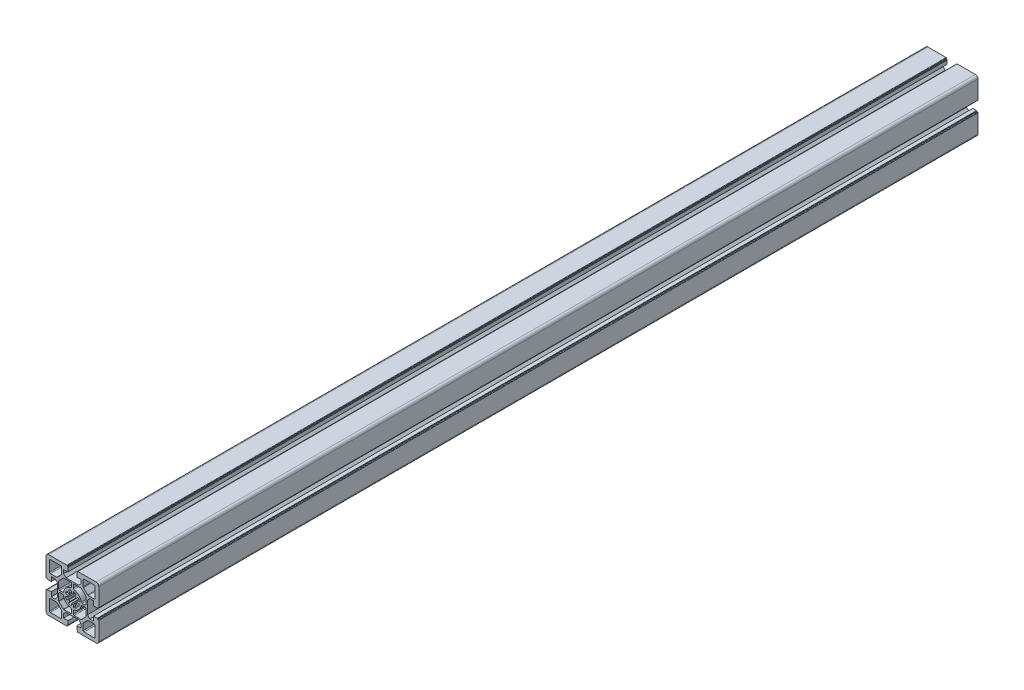
SolidWorks part; units mm, degrees
ref_plane "Front Plane" through (0, 0, 0) normal (0, 0, 1) x (1, 0, 0)
ref_plane "Top Plane" through (0, 0, 0) normal (0, 1, 0) x (1, 0, 0)
ref_plane "Right Plane" through (0, 0, 0) normal (1, 0, 0) x (0, 0, -1)
sketch "Sketch1" plane through (0, 0, 0) normal (0, 0, 1) x (1, 0, 0)
  line L0 (25, 12.3) -> (17.9642, 12.3)
  line L1 (17.2571, 12.5929) -> (12.5929, 17.2571)
  line L2 (12.3, 17.9642) -> (12.3, 25)
  line L3 (25, 26) -> (13.3, 26)
  line L4 (26, 13.3) -> (26, 25)
  line L5 (-0.8683, 4.924) -> (-1.3892, 7.8785)
  line L6 (-4.5886, 6.5532) -> (-2.8679, 4.0958)
  line L7 (-4.0958, 2.8679) -> (-6.5532, 4.5886)
  line L8 (-7.8785, 1.3892) -> (-4.9241, 0.8683)
  line L9 (14.5, 1) -> (10.9691, 1)
  line L10 (15.5, 2) -> (15.5, 9.9003)
  line L11 (15.3535, 10.2538) -> (10.2538, 15.3536)
  line L12 (9.9002, 15.5) -> (2, 15.5)
  line L13 (1, 10.9692) -> (1, 14.5)
  line L14 (7.25, 17) -> (0, 17)
  line L15 (10.05, 19.8) -> (7.25, 17)
  line L16 (10.05, 24) -> (10.05, 19.8)
  line L17 (5, 24) -> (10.05, 24)
  line L18 (5, 28.2) -> (5, 24)
  line L19 (5.5, 28.5) -> (5.3, 28.5)
  line L20 (5.8, 28.8) -> (5.8, 29.5)
  line L21 (27, 30) -> (6.3, 30)
  line L22 (30, 6.3) -> (30, 27)
  line L23 (29.5, 5.8) -> (28.8, 5.8)
  line L24 (28.5, 5.3) -> (28.5, 5.5)
  line L25 (24, 5) -> (28.2, 5)
  line L26 (24, 10.05) -> (24, 5)
  line L27 (19.8, 10.05) -> (24, 10.05)
  line L28 (17, 7.25) -> (19.8, 10.05)
  line L29 (17, 7.25) -> (17, 0)
  line L30 (7.8784, 1.3892) -> (4.924, 0.8683)
  line L31 (4.0957, 2.8679) -> (6.5532, 4.5886)
  line L32 (4.5886, 6.5532) -> (2.8679, 4.0958)
  line L33 (0.8682, 4.924) -> (1.3892, 7.8785)
  line L34 (-25, -12.3) -> (-17.9642, -12.3)
  line L35 (-17.2571, -12.5929) -> (-12.5929, -17.2571)
  line L36 (-12.3, -17.9642) -> (-12.3, -25)
  line L37 (-25, -26) -> (-13.3, -26)
  line L38 (-26, -13.3) -> (-26, -25)
  line L39 (-14.5, -1) -> (-10.9692, -1)
  line L40 (-15.5, -2) -> (-15.5, -9.9002)
  line L41 (-17, 7.25) -> (-17, 0)
  line L42 (-17, 7.25) -> (-19.8, 10.05)
  line L43 (-19.8, 10.05) -> (-24, 10.05)
  line L44 (-24, 10.05) -> (-24, 5)
  line L45 (-24, 5) -> (-28.2, 5)
  line L46 (-28.5, 5.3) -> (-28.5, 5.5)
  line L47 (-29.5, 5.8) -> (-28.8, 5.8)
  line L48 (-30, 6.3) -> (-30, 27)
  line L49 (-27, 30) -> (-6.3, 30)
  line L50 (-5.8, 28.8) -> (-5.8, 29.5)
  line L51 (-5.5, 28.5) -> (-5.3, 28.5)
  line L52 (-5, 28.2) -> (-5, 24)
  line L53 (-5, 24) -> (-10.05, 24)
  line L54 (-10.05, 24) -> (-10.05, 19.8)
  line L55 (-10.05, 19.8) -> (-7.25, 17)
  line L56 (-7.25, 17) -> (0, 17)
  line L57 (-15.3536, -10.2538) -> (-10.2538, -15.3535)
  line L58 (-9.9003, -15.5) -> (-2, -15.5)
  line L59 (-1, -10.9691) -> (-1, -14.5)
  line L60 (-7.25, -17) -> (0, -17)
  line L61 (-10.05, -19.8) -> (-7.25, -17)
  line L62 (-10.05, -24) -> (-10.05, -19.8)
  line L63 (-5, -24) -> (-10.05, -24)
  line L64 (-5, -28.2) -> (-5, -24)
  line L65 (-5.5, -28.5) -> (-5.3, -28.5)
  line L66 (-5.8, -28.8) -> (-5.8, -29.5)
  line L67 (-27, -30) -> (-6.3, -30)
  line L68 (-30, -6.3) -> (-30, -27)
  line L69 (-29.5, -5.8) -> (-28.8, -5.8)
  line L70 (-28.5, -5.3) -> (-28.5, -5.5)
  line L71 (-24, -5) -> (-28.2, -5)
  line L72 (-24, -10.05) -> (-24, -5)
  line L73 (-19.8, -10.05) -> (-24, -10.05)
  line L74 (-17, -7.25) -> (-19.8, -10.05)
  line L75 (-17, 0) -> (-17, -7.25)
  line L76 (0.8682, -4.924) -> (1.3892, -7.8784)
  line L77 (4.5886, -6.5532) -> (2.8679, -4.0957)
  line L78 (4.0957, -2.8679) -> (6.5532, -4.5886)
  line L79 (7.8784, -1.3892) -> (4.924, -0.8682)
  line L80 (17, 0) -> (17, -7.25)
  line L81 (17, -7.25) -> (19.8, -10.05)
  line L82 (19.8, -10.05) -> (24, -10.05)
  line L83 (24, -10.05) -> (24, -5)
  line L84 (24, -5) -> (28.2, -5)
  line L85 (28.5, -5.3) -> (28.5, -5.5)
  line L86 (29.5, -5.8) -> (28.8, -5.8)
  line L87 (30, -6.3) -> (30, -27)
  line L88 (27, -30) -> (6.3, -30)
  line L89 (5.8, -28.8) -> (5.8, -29.5)
  line L90 (5.5, -28.5) -> (5.3, -28.5)
  line L91 (5, -28.2) -> (5, -24)
  line L92 (5, -24) -> (10.05, -24)
  line L93 (10.05, -24) -> (10.05, -19.8)
  line L94 (10.05, -19.8) -> (7.25, -17)
  line L95 (7.25, -17) -> (0, -17)
  line L96 (1, -10.9691) -> (1, -14.5)
  line L97 (9.9002, -15.5) -> (2, -15.5)
  line L98 (15.3535, -10.2538) -> (10.2538, -15.3535)
  line L99 (15.5, -2) -> (15.5, -9.9002)
  line L100 (-1, 10.9692) -> (-1, 14.5)
  line L101 (-9.9003, 15.5) -> (-2, 15.5)
  line L102 (-15.3536, 10.2538) -> (-10.2538, 15.3536)
  line L103 (-15.5, 2) -> (-15.5, 9.9003)
  line L104 (-14.5, 1) -> (-10.9692, 1)
  line L105 (-26, 13.3) -> (-26, 25)
  line L106 (-25, 26) -> (-13.3, 26)
  line L107 (-12.3, 17.9642) -> (-12.3, 25)
  line L108 (-17.2571, 12.5929) -> (-12.5929, 17.2571)
  line L109 (-25, 12.3) -> (-17.9642, 12.3)
  line L110 (14.5, -1) -> (10.9691, -1)
  line L111 (-7.8785, -1.3892) -> (-4.9241, -0.8682)
  line L112 (-4.0958, -2.8679) -> (-6.5532, -4.5886)
  line L113 (-4.5886, -6.5532) -> (-2.8679, -4.0957)
  line L114 (-0.8683, -4.924) -> (-1.3892, -7.8784)
  line L115 (26, -13.3) -> (26, -25)
  line L116 (25, -26) -> (13.3, -26)
  line L117 (12.3, -17.9642) -> (12.3, -25)
  line L118 (17.2571, -12.5929) -> (12.5929, -17.2571)
  line L119 (25, -12.3) -> (17.9642, -12.3)
  line L120 (0, 0) -> (0, 50.387) construction
  line L121 (0, 0) -> (0, -41.9308) construction
  line L122 (0, 0) -> (51.9943, 0) construction
  line L123 (0, 0) -> (-54.8745, 0) construction
  arc A0 (17.9642, 12.3) -> (17.2571, 12.5929) centre (17.9642, 13.3) cw
  arc A1 (12.5929, 17.2571) -> (12.3, 17.9642) centre (13.3, 17.9642) cw
  arc A2 (12.3, 25) -> (13.3, 26) centre (13.3, 25) cw
  arc A3 (25, 26) -> (26, 25) centre (25, 25) cw
  arc A4 (26, 13.3) -> (25, 12.3) centre (25, 13.3) cw
  arc A5 (0, 5) -> (-0.8683, 4.924) centre (0, 0) ccw
  arc A6 (-1.3892, 7.8785) -> (-4.5886, 6.5532) centre (0, 0) ccw
  arc A7 (-2.8679, 4.0958) -> (-4.0958, 2.8679) centre (0, 0) ccw
  arc A8 (-6.5532, 4.5886) -> (-7.8785, 1.3892) centre (0, 0) ccw
  arc A9 (-4.9241, 0.8683) -> (-4.9241, -0.8682) centre (0, 0) ccw
  arc A10 (15.5, 2) -> (14.5, 1) centre (14.5, 2) cw
  arc A11 (15.3535, 10.2538) -> (15.5, 9.9003) centre (15, 9.9003) cw
  arc A12 (9.9002, 15.5) -> (10.2538, 15.3536) centre (9.9002, 15) cw
  arc A13 (1, 14.5) -> (2, 15.5) centre (2, 14.5) cw
  arc A14 (1.8206, 9.9854) -> (1, 10.9692) centre (2, 10.9692) cw
  arc A15 (1.8206, 9.9854) -> (9.9853, 1.8206) centre (0, 0) cw
  arc A16 (10.9691, 1) -> (9.9853, 1.8206) centre (10.9691, 2) cw
  arc A17 (5, 28.2) -> (5.3, 28.5) centre (5.3, 28.2) cw
  arc A18 (5.8, 28.8) -> (5.5, 28.5) centre (5.5, 28.8) cw
  arc A19 (5.8, 29.5) -> (6.3, 30) centre (6.3, 29.5) cw
  arc A20 (27, 30) -> (30, 27) centre (27, 27) cw
  arc A21 (30, 6.3) -> (29.5, 5.8) centre (29.5, 6.3) cw
  arc A22 (28.5, 5.5) -> (28.8, 5.8) centre (28.8, 5.5) cw
  arc A23 (28.5, 5.3) -> (28.2, 5) centre (28.2, 5.3) cw
  arc A24 (4.924, 0.8683) -> (4.924, -0.8682) centre (0, 0) cw
  arc A25 (6.5532, 4.5886) -> (7.8784, 1.3892) centre (0, 0) cw
  arc A26 (2.8679, 4.0958) -> (4.0957, 2.8679) centre (0, 0) cw
  arc A27 (1.3892, 7.8785) -> (4.5886, 6.5532) centre (0, 0) cw
  arc A28 (-28.5, 5.3) -> (-28.2, 5) centre (-28.2, 5.3) ccw
  arc A29 (-28.5, 5.5) -> (-28.8, 5.8) centre (-28.8, 5.5) ccw
  arc A30 (-30, 6.3) -> (-29.5, 5.8) centre (-29.5, 6.3) ccw
  arc A31 (-27, 30) -> (-30, 27) centre (-27, 27) ccw
  arc A32 (-5.8, 29.5) -> (-6.3, 30) centre (-6.3, 29.5) ccw
  arc A33 (-5.8, 28.8) -> (-5.5, 28.5) centre (-5.5, 28.8) ccw
  arc A34 (-5, 28.2) -> (-5.3, 28.5) centre (-5.3, 28.2) ccw
  arc A35 (0, 5) -> (0.8682, 4.924) centre (0, 0) cw
  arc A36 (-17.9642, -12.3) -> (-17.2571, -12.5929) centre (-17.9642, -13.3) cw
  arc A37 (-12.5929, -17.2571) -> (-12.3, -17.9642) centre (-13.3, -17.9642) cw
  arc A38 (-12.3, -25) -> (-13.3, -26) centre (-13.3, -25) cw
  arc A39 (-25, -26) -> (-26, -25) centre (-25, -25) cw
  arc A40 (-26, -13.3) -> (-25, -12.3) centre (-25, -13.3) cw
  arc A41 (-15.5, -2) -> (-14.5, -1) centre (-14.5, -2) cw
  arc A42 (-15.3536, -10.2538) -> (-15.5, -9.9002) centre (-15, -9.9002) cw
  arc A43 (-9.9003, -15.5) -> (-10.2538, -15.3535) centre (-9.9003, -15) cw
  arc A44 (-1, -14.5) -> (-2, -15.5) centre (-2, -14.5) cw
  arc A45 (-1.8206, -9.9853) -> (-1, -10.9691) centre (-2, -10.9691) cw
  arc A46 (-1.8206, -9.9853) -> (-9.9854, -1.8206) centre (0, 0) cw
  arc A47 (-10.9692, -1) -> (-9.9854, -1.8206) centre (-10.9692, -2) cw
  arc A48 (0, -4.9999) -> (0.8682, -4.924) centre (0, 0) ccw
  arc A49 (-5, -28.2) -> (-5.3, -28.5) centre (-5.3, -28.2) cw
  arc A50 (-5.8, -28.8) -> (-5.5, -28.5) centre (-5.5, -28.8) cw
  arc A51 (-5.8, -29.5) -> (-6.3, -30) centre (-6.3, -29.5) cw
  arc A52 (-27, -30) -> (-30, -27) centre (-27, -27) cw
  arc A53 (-30, -6.3) -> (-29.5, -5.8) centre (-29.5, -6.3) cw
  arc A54 (-28.5, -5.5) -> (-28.8, -5.8) centre (-28.8, -5.5) cw
  arc A55 (-28.5, -5.3) -> (-28.2, -5) centre (-28.2, -5.3) cw
  arc A56 (1.3892, -7.8784) -> (4.5886, -6.5532) centre (0, 0) ccw
  arc A57 (2.8679, -4.0957) -> (4.0957, -2.8679) centre (0, 0) ccw
  arc A58 (6.5532, -4.5886) -> (7.8784, -1.3892) centre (0, 0) ccw
  arc A59 (28.5, -5.3) -> (28.2, -5) centre (28.2, -5.3) ccw
  arc A60 (28.5, -5.5) -> (28.8, -5.8) centre (28.8, -5.5) ccw
  arc A61 (30, -6.3) -> (29.5, -5.8) centre (29.5, -6.3) ccw
  arc A62 (27, -30) -> (30, -27) centre (27, -27) ccw
  arc A63 (5.8, -29.5) -> (6.3, -30) centre (6.3, -29.5) ccw
  arc A64 (5.8, -28.8) -> (5.5, -28.5) centre (5.5, -28.8) ccw
  arc A65 (5, -28.2) -> (5.3, -28.5) centre (5.3, -28.2) ccw
  arc A66 (10.9691, -1) -> (9.9853, -1.8206) centre (10.9691, -2) ccw
  arc A67 (1.8206, -9.9853) -> (9.9853, -1.8206) centre (0, 0) ccw
  arc A68 (-10.9692, 1) -> (-9.9854, 1.8206) centre (-10.9692, 2) ccw
  arc A69 (-1.8206, 9.9854) -> (-9.9854, 1.8206) centre (0, 0) ccw
  arc A70 (-1.8206, 9.9854) -> (-1, 10.9692) centre (-2, 10.9692) ccw
  arc A71 (-1, 14.5) -> (-2, 15.5) centre (-2, 14.5) ccw
  arc A72 (-9.9003, 15.5) -> (-10.2538, 15.3536) centre (-9.9003, 15) ccw
  arc A73 (-15.3536, 10.2538) -> (-15.5, 9.9003) centre (-15, 9.9003) ccw
  arc A74 (-15.5, 2) -> (-14.5, 1) centre (-14.5, 2) ccw
  arc A75 (-26, 13.3) -> (-25, 12.3) centre (-25, 13.3) ccw
  arc A76 (-25, 26) -> (-26, 25) centre (-25, 25) ccw
  arc A77 (-12.3, 25) -> (-13.3, 26) centre (-13.3, 25) ccw
  arc A78 (-12.5929, 17.2571) -> (-12.3, 17.9642) centre (-13.3, 17.9642) ccw
  arc A79 (-17.9642, 12.3) -> (-17.2571, 12.5929) centre (-17.9642, 13.3) ccw
  arc A80 (1.8206, -9.9853) -> (1, -10.9691) centre (2, -10.9691) ccw
  arc A81 (1, -14.5) -> (2, -15.5) centre (2, -14.5) ccw
  arc A82 (9.9002, -15.5) -> (10.2538, -15.3535) centre (9.9002, -15) ccw
  arc A83 (15.3535, -10.2538) -> (15.5, -9.9002) centre (15, -9.9002) ccw
  arc A84 (15.5, -2) -> (14.5, -1) centre (14.5, -2) ccw
  arc A85 (-6.5532, -4.5886) -> (-7.8785, -1.3892) centre (0, 0) cw
  arc A86 (-2.8679, -4.0957) -> (-4.0958, -2.8679) centre (0, 0) cw
  arc A87 (-1.3892, -7.8784) -> (-4.5886, -6.5532) centre (0, 0) cw
  arc A88 (0, -4.9999) -> (-0.8683, -4.924) centre (0, 0) cw
  arc A89 (26, -13.3) -> (25, -12.3) centre (25, -13.3) ccw
  arc A90 (25, -26) -> (26, -25) centre (25, -25) ccw
  arc A91 (12.3, -25) -> (13.3, -26) centre (13.3, -25) ccw
  arc A92 (12.5929, -17.2571) -> (12.3, -17.9642) centre (13.3, -17.9642) ccw
  arc A93 (17.9642, -12.3) -> (17.2571, -12.5929) centre (17.9642, -13.3) ccw
  dimension "D6" = 13
  dimension "D4" = 10
  dimension "D1" = 60
  dimension "D2" = 60
  dimension "D3" = 30
  dimension "D5" = 10
extrude "Base-Extrude" add sketch "Sketch1" against normal blind 1000
scale "Escala1" scale about origin uniform scaling yes scale factor 0.5
